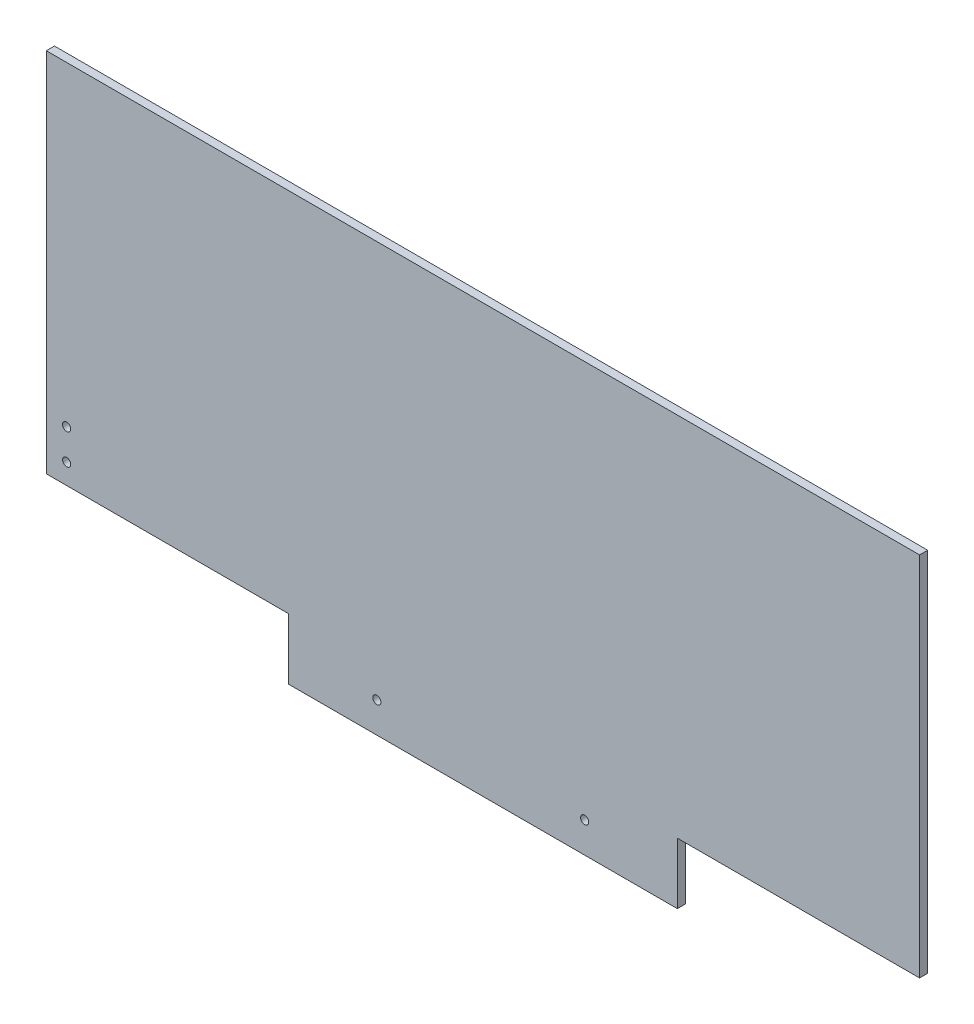
SolidWorks part; units mm, degrees
ref_plane "Front Plane" through (0, 0, 0) normal (0, 0, 1) x (1, 0, 0)
ref_plane "Top Plane" through (0, 0, 0) normal (0, 1, 0) x (1, 0, 0)
ref_plane "Right Plane" through (0, 0, 0) normal (1, 0, 0) x (0, 0, -1)
sketch "Sketch1" plane through (0, 0, 0) normal (0, 0, 1) x (1, 0, 0)
  line L1 (-214.5, 105) -> (214.5, 105)
  line L2 (-214.5, 105) -> (-214.5, -105)
  line L3 (-214.5, -105) -> (214.5, -105)
  line L4 (214.5, 105) -> (214.5, -105)
  line L5 (-214.5, 105) -> (214.5, -105) construction
  line L6 (-214.5, -105) -> (214.5, 105) construction
  point P0 (0, 0)
  dimension "D1" = 429
  dimension "D2" = 210
extrude "Boss-Extrude1" add sketch "Sketch1" along normal blind 4
sketch "Sketch2" plane through (0, 0, 0) normal (0, 0, -1) x (-1, 0, 0)
  line L0 (-214.5, -75) -> (-95.5, -75)
  line L1 (-214.5, -105) -> (-214.5, 105) construction
  line L2 (-95.5, -75) -> (-95.5, -105)
  line L3 (214.5, -105) -> (-214.5, -105) construction
  line L4 (214.5, -75) -> (95.5, -75)
  line L5 (214.5, 105) -> (214.5, -105) construction
  line L6 (95.5, -75) -> (95.5, -105)
  line L7 (-214.5, -75) -> (-214.5, -105)
  line L8 (-214.5, -105) -> (-95.5, -105)
  line L9 (214.5, -75) -> (214.5, -105)
  line L10 (214.5, -105) -> (95.5, -105)
  dimension "D1" = 30
  dimension "D2" = 95.5
  dimension "D3" = 95.5
extrude "Cut-Extrude1" cut sketch "Sketch2" against normal blind 4
sketch "Sketch3" plane through (0, 0, 0) normal (0, 0, -1) x (-1, 0, 0)
  line L0 (95.5, -105) -> (-95.5, -105) construction
  circle A0 centre (-49.9836, -90) radius 2
  circle A1 centre (52.1258, -90) radius 2
  dimension "D1" = 4
  dimension "D2" = 4
  dimension "D3" = 15
  dimension "D4" = 15
extrude "Cut-Extrude2" cut sketch "Sketch3" against normal through all
sketch "Sketch4" plane through (0, 0, 0) normal (0, 0, -1) x (-1, 0, 0)
  line L0 (214.5, -75) -> (95.5, -75) construction
  line L1 (214.5, 105) -> (214.5, -75) construction
  circle A0 centre (204.5, -65) radius 2
  circle A1 centre (204.5, -50) radius 2
  dimension "D1" = 4
  dimension "D2" = 4
  dimension "D3" = 10
  dimension "D4" = 25
  dimension "D5" = 10
  dimension "D6" = 10
extrude "Cut-Extrude3" cut sketch "Sketch4" against normal through all
